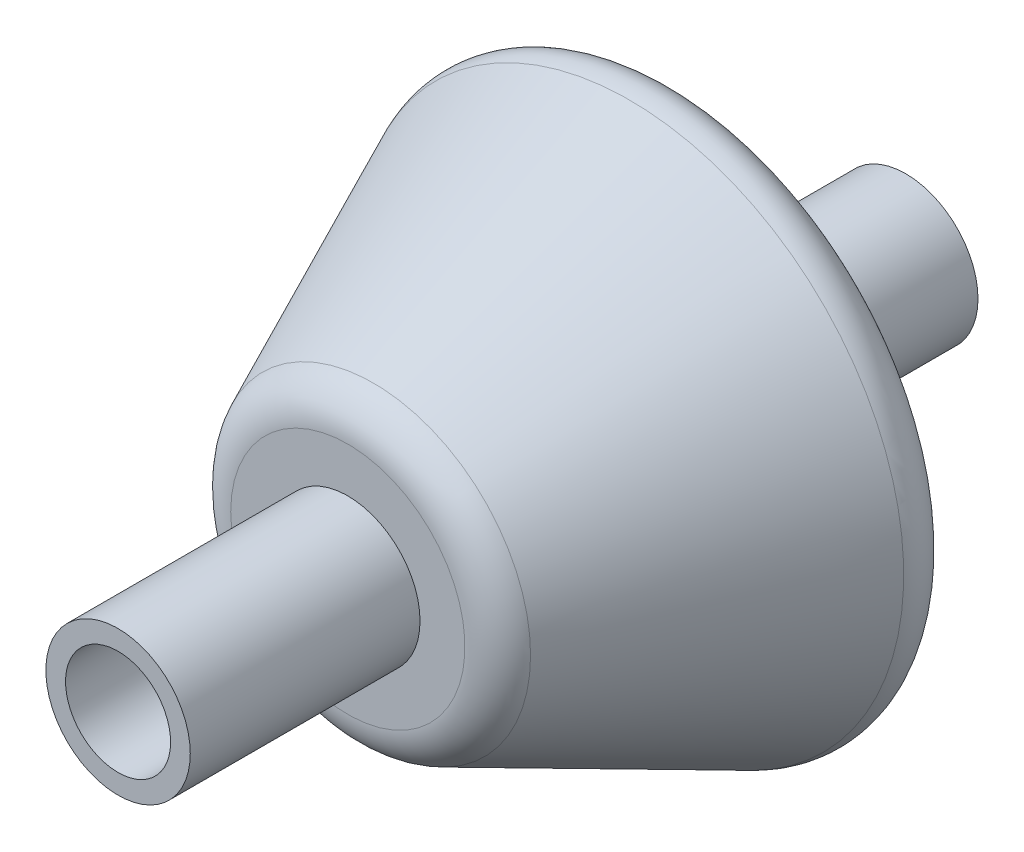
SolidWorks part; units mm, degrees
ref_plane "Front Plane" through (0, 0, 0) normal (0, 0, 1) x (1, 0, 0)
ref_plane "Top Plane" through (0, 0, 0) normal (0, 1, 0) x (1, 0, 0)
ref_plane "Right Plane" through (0, 0, 0) normal (1, 0, 0) x (0, 0, -1)
sketch "Sketch1" plane through (0, 0, 0) normal (0, 0, 1) x (1, 0, 0)
  circle A0 centre (0, 0) radius 8
  circle A1 centre (0, 0) radius 11
  dimension "D1" = 22
  dimension "D2" = 16
extrude "Boss-Extrude1" add sketch "Sketch1" along normal mid plane 120
sketch "Sketch2" plane through (0, 0, 0) normal (1, 0, 0) x (0, 0, -1)
  line L0 (-25, 0) -> (-25, 17.8403)
  line L1 (-21.0888, 23.929) -> (17.9211, 41.7636)
  line L2 (25, 37.2163) -> (25, 0)
  line L3 (25, 0) -> (-25, 0) construction
  line L4 (-25, 0) -> (25, 0)
  arc A1 (-25, 17.8403) -> (-21.0888, 23.929) centre (-18.3051, 17.8403) cw
  arc A2 (25, 37.2163) -> (17.9211, 41.7636) centre (20, 37.2163) ccw
  point P2 (-22.8689, 0)
  point P3 (-25, 10.3374)
  point P8 (8.9351, 0)
  point P9 (-11.1899, 0)
  point P10 (-6.8484, 51.2962)
  point P11 (-10.7051, 1.2106)
  point P13 (0, 0)
  point P14 (-23.6037, 3.6548)
  point P15 (0, 0)
  point P16 (0, 0)
  point P17 (-25, 17.8403)
  point P20 (25, 45)
  dimension "D1" = 50
  dimension "D2" = 5
  dimension "D3" = 45
revolve "Revolve1" add sketch "Sketch2" angle 360 about L3
